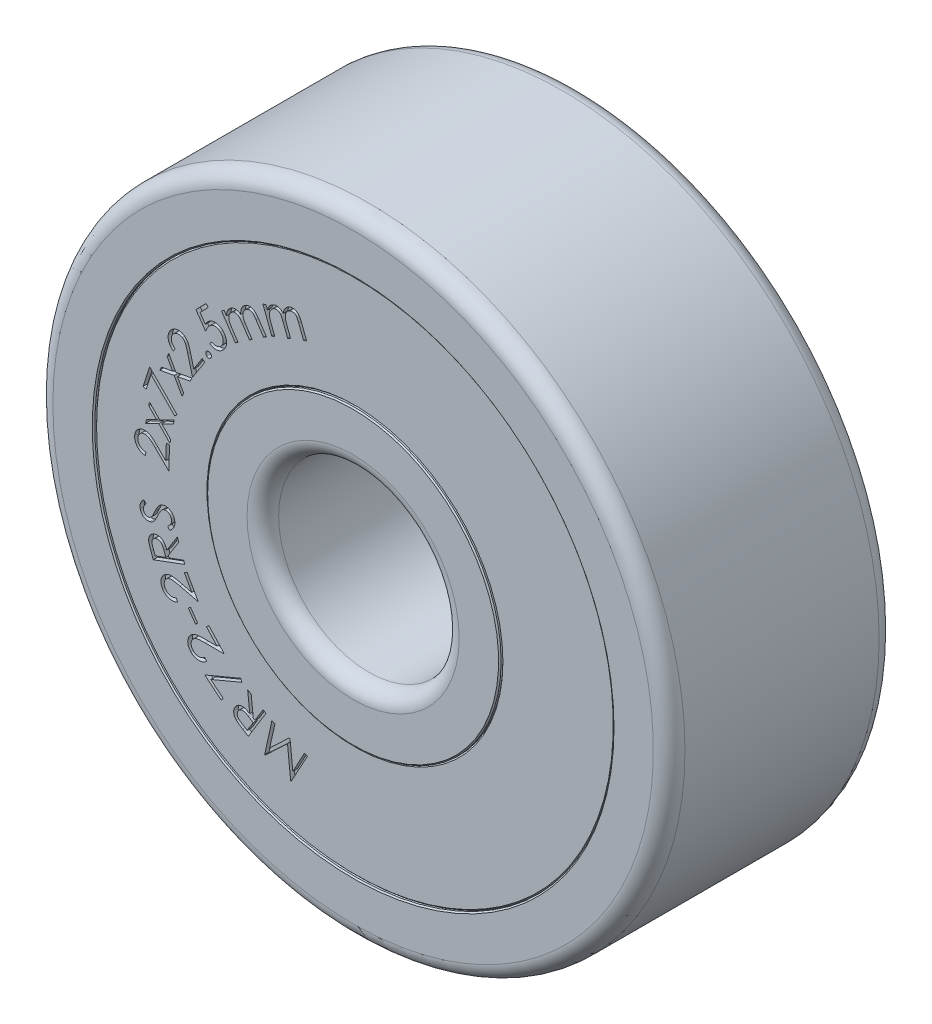
SolidWorks part; units mm, degrees
material "AISI 316 Annealed Stainless Steel Bar (SS)"
ref_plane "Front" through (0, 0, 0) normal (0, 0, 1) x (1, 0, 0)
ref_plane "Top" through (0, 0, 0) normal (0, 1, 0) x (1, 0, 0)
ref_plane "Right" through (0, 0, 0) normal (1, 0, 0) x (0, 0, -1)
sketch "LAYOUT R" plane through (0, 0, 0) normal (1, 0, 0) x (0, 0, -1)
  line L0 (-1.25, 1) -> (1.25, 1)
  line L1 (1.25, -3.5) -> (-1.25, -3.5) construction
  line L2 (1.25, -3.5) -> (1.25, 3.5) construction
  line L3 (1.25, 3.5) -> (-1.25, 3.5)
  line L4 (-1.25, -3.5) -> (-1.25, 3.5) construction
  line L5 (1.25, -3.5) -> (-1.25, 3.5) construction
  line L6 (1.25, 3.5) -> (-1.25, -3.5) construction
  line L7 (-1.25, 1.625) -> (1.25, 1.625)
  line L8 (-1.25, 2.875) -> (1.25, 2.875)
  line L11 (-17.5, 0) -> (17.5, 0) construction
  line L12 (-1.25, 3.5) -> (-1.25, 2.875)
  line L13 (1.25, 3.5) -> (1.25, 2.875)
  line L14 (-1.25, 2.875) -> (-1.25, 1.625)
  line L15 (1.25, 2.875) -> (1.25, 1.625)
  line L16 (-1.25, 1.625) -> (-1.25, 1)
  line L17 (1.25, 1.625) -> (1.25, 1)
  line L18 (-1.23, 2.875) -> (-1.23, 1.625)
  line L19 (1.23, 2.875) -> (1.23, 1.625)
  point P0 (0, 0)
  point P15 (0, 0)
  dimension "D1" = 2.5
  dimension "D2" = 7
  dimension "D3" = 1
  dimension "D6" = 0.02
  dimension "D7" = 0.02
  dimension "D4" = 1.625
  dimension "D5" = 2.875
sketch "Sketch R, INNER BODY" plane through (0, 0, 0) normal (1, 0, 0) x (0, 0, -1)
  line L0 (-1.25, 1) -> (1.25, 1) construction
  line L2 (-1.25, 1.625) -> (1.25, 1.625) construction
  line L4 (-1.25, 1) -> (1.25, 1)
  line L6 (-1.25, 1.625) -> (1.25, 1.625)
  line L8 (1.25, 1.625) -> (1.25, 1) construction
  line L9 (-1.25, 1.625) -> (-1.25, 1) construction
  line L10 (1.25, 1.625) -> (1.25, 1)
  line L11 (-1.25, 1.625) -> (-1.25, 1)
  line L12 (-17.5, 0) -> (17.5, 0) construction
  line L13 (-17.5, 0) -> (17.5, 0) construction
sketch "Sketch R, OUTER BODY" plane through (0, 0, 0) normal (1, 0, 0) x (0, 0, -1)
  line L2 (-1.25, 2.875) -> (1.25, 2.875) construction
  line L3 (1.25, 3.5) -> (-1.25, 3.5) construction
  line L6 (-1.25, 2.875) -> (1.25, 2.875)
  line L7 (1.25, 3.5) -> (-1.25, 3.5)
  line L8 (-17.5, 0) -> (17.5, 0) construction
  line L9 (-17.5, 0) -> (17.5, 0) construction
  line L10 (1.25, 3.5) -> (1.25, 2.875) construction
  line L11 (-1.25, 3.5) -> (-1.25, 2.875) construction
  line L12 (1.25, 3.5) -> (1.25, 2.875)
  line L13 (-1.25, 3.5) -> (-1.25, 2.875)
sketch "Sketch R, SEAL FACES" plane through (0, 0, 0) normal (1, 0, 0) x (0, 0, -1)
  line L0 (-17.5, 0) -> (17.5, 0) construction
  line L1 (-17.5, 0) -> (17.5, 0) construction
  line L3 (-1.25, 1.625) -> (1.25, 1.625) construction
  line L5 (-1.25, 2.875) -> (1.25, 2.875) construction
  line L7 (-1.23, 1.625) -> (1.23, 1.625)
  line L9 (-1.23, 2.875) -> (1.23, 2.875)
  line L10 (1.23, 2.875) -> (1.23, 1.625) construction
  line L11 (-1.23, 2.875) -> (-1.23, 1.625) construction
  line L12 (1.23, 2.875) -> (1.23, 1.625)
  line L13 (-1.23, 2.875) -> (-1.23, 1.625)
revolve "Revolve INNER BODY" add sketch "Sketch R, INNER BODY" angle 360 about L13
fillet "Fillet INNER BODY" radius 0.175 2 edges at (1, 0, 1.25) (1, 0, -1.25)
chamfer "Chamfer INNER BODY" distance 0.014 angle 45 2 edges at (1.625, 0, -1.25) (1.625, 0, 1.25)
revolve "Revolve OUTER BODY" add sketch "Sketch R, OUTER BODY" angle 360 about L9
fillet "Fillet OUTER BODY" radius 0.175 2 edges at (3.5, 0, -1.25) (3.5, 0, 1.25)
chamfer "Chamfer OUTER BODY" distance 0.014 angle 45 2 edges at (2.875, 0, 1.25) (2.875, 0, -1.25)
revolve "Revolve SEALS" add sketch "Sketch R, SEAL FACES" angle 360 about L1
chamfer "Chamfer SEALS" distance 0.014 angle 45 4 edges at (1.625, 0, -1.23) (2.875, 0, -1.23) (2.875, 0, 1.23) (1.625, 0, 1.23)
sketch "Sketch TEXT RADIUS 1 — MANUALLY ASSIGN TEXT AND FONT SIZE (FROM EQUATIONS)" plane through (0, 0, 1.23) normal (0, 0, 1) x (1, 0, 0)
  circle A0 centre (0, 0) radius 2.0625 construction
  text T0 "MR72-2RS  2x7x2.5mm" font "Century Gothic" height 0.375
  dimension "D1" = 4.125
extrude "Cut-Extrude SEAL LABEL 1" cut sketch "Sketch TEXT RADIUS 1 — MANUALLY ASSIGN TEXT AND FONT SIZE (FROM EQUATIONS)" against normal blind 0.05
sketch "Sketch TEXT RADIUS 2 — MANUALLY ASSIGN TEXT AND FONT SIZE (FROM EQUATIONS)" plane through (0, 0, -1.23) normal (0, 0, -1) x (-1, 0, 0)
  circle A0 centre (0, 0) radius 2.0625 construction
  text T0 "MR72-2RS  2x7x2.5mm" font "Century Gothic" height 0.375
  dimension "D1" = 4.125
extrude "Cut-Extrude SEAL LABEL 2" cut sketch "Sketch TEXT RADIUS 2 — MANUALLY ASSIGN TEXT AND FONT SIZE (FROM EQUATIONS)" against normal blind 0.05
equation "\"_i__BORE\"= 2"
equation "\"_i__OUTSIDE_DIAMETER\"= 7"
equation "\"_i__WIDTH\"= 2.5"
equation "\"_i_optional__TEXT_RADIUS_ADJUSTMENT\"= 0"
equation "\"_output__FONT_SIZE_mm\"= \"BODY_SPAN__SEAL__OF_RADIUS\" * \"param__FONT_SIZE_RATIO\"'MANUALLY ASSIGN TO FONT"
equation "\"BODY__HALF_WIDTH\"= \"_i__WIDTH\" / 2"
equation "\"BODY_SPAN___OF_DIAMETER\"= \"_i__OUTSIDE_DIAMETER\" - \"_i__BORE\""
equation "\"BODY_SPAN___OF_RADIUS\"= \"BODY_SPAN___OF_DIAMETER\" / 2"
equation "\"BODY_SPAN__BORE_AND_OD__OF RADIUS\"= ( \"BODY_SPAN___OF_RADIUS\" - \"BODY_SPAN__SEAL__OF_RADIUS\" ) / 2"
equation "\"BODY_SPAN__SEAL__OF_RADIUS\"= \"BODY_SPAN___OF_RADIUS\" * \"param__SEAL_PANEL_SPAN__RATIO_OF_BODY_RADIAN\""
equation "\"BORE__RADIUS\"= \"_i__BORE\" / 2"
equation "\"CORNER_RADII\"= \"_i__WIDTH\" * \"param__CORNER_RADII__ISO_MAX_RATIO_TO_WIDTH\""
equation "\"param__CORNER_RADII__ISO_MAX_RATIO_TO_WIDTH\"= 0.07'WHERE WIDTH IS LESS THAN DIAMETER"
equation "\"param__FONT_SIZE_RATIO\"= 0.3"
equation "\"param__SEAL_FACE_INSET__RATIO_OF_WIDTH\"= .01"
equation "\"param__SEAL_PANEL_SPAN__RATIO_OF_BODY_RADIAN\"= 0.5"
equation "\"param__SIDE_CHAMFERS__RATIO_TO_OD\"= 1 / 500"
equation "\"RING_INNER__OUTSIDE_RADIUS\"= \"BORE__RADIUS\" + \"BODY_SPAN__BORE_AND_OD__OF RADIUS\""
equation "\"RING_OUTER__OUTSIDE_RADIUS\"= ( \"_i__OUTSIDE_DIAMETER\" / 2 ) - \"BODY_SPAN__BORE_AND_OD__OF RADIUS\""
equation "\"SEAL_FACE_INSET\"= \"_i__WIDTH\" * \"param__SEAL_FACE_INSET__RATIO_OF_WIDTH\""
equation "\"SIDE_FACE_AND_SEAL_CHAMFERS\"= \"_i__OUTSIDE_DIAMETER\" * \"param__SIDE_CHAMFERS__RATIO_TO_OD\""
equation "\"TEXT_RADIUS\"= \"_i__BORE\" + ( \"BODY_SPAN___OF_DIAMETER\" / 2 ) - \"_output__FONT_SIZE_mm\" + \"_i_optional__TEXT_RADIUS_ADJUSTMENT\""
equation "\"D1@Chamfer INNER BODY\"=\"SIDE_FACE_AND_SEAL_CHAMFERS\""
equation "\"D1@Chamfer OUTER BODY\"=\"SIDE_FACE_AND_SEAL_CHAMFERS\""
equation "\"D1@Chamfer SEALS\"=\"SIDE_FACE_AND_SEAL_CHAMFERS\""
equation "\"D1@Fillet INNER BODY\"=\"CORNER_RADII\""
equation "\"D1@Fillet OUTER BODY\"=\"CORNER_RADII\""
equation "\"D1@LAYOUT R\"=\"_i__WIDTH\""
equation "\"D1@Sketch TEXT RADIUS 1 — MANUALLY ASSIGN TEXT AND FONT SIZE (FROM EQUATIONS)\" = \"TEXT_RADIUS\""
equation "\"D1@Sketch TEXT RADIUS 2 — MANUALLY ASSIGN TEXT AND FONT SIZE (FROM EQUATIONS)\" = \"TEXT_RADIUS\""
equation "\"D2@LAYOUT R\"=\"_i__OUTSIDE_DIAMETER\""
equation "\"D3@LAYOUT R\"=\"BORE__RADIUS\""
equation "\"D4@LAYOUT R\"=\"RING_INNER__OUTSIDE_RADIUS\""
equation "\"D5@LAYOUT R\"=\"RING_OUTER__OUTSIDE_RADIUS\""
